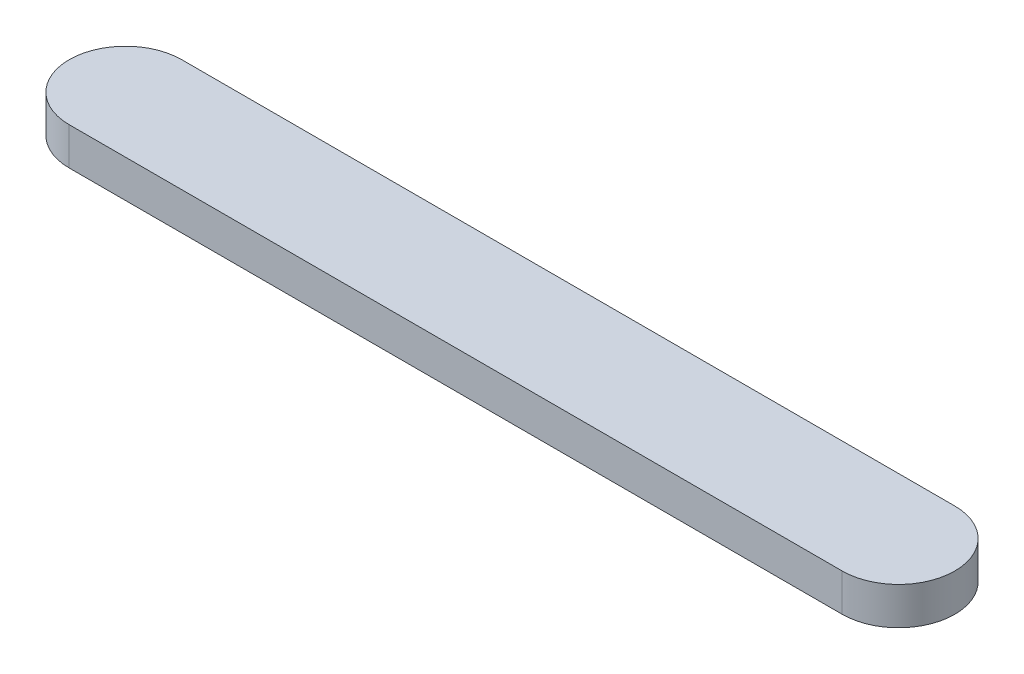
SolidWorks part; units mm, degrees
ref_plane "Plan de face" through (0, 0, 0) normal (0, 0, 1) x (1, 0, 0)
ref_plane "Plan de dessus" through (0, 0, 0) normal (0, 1, 0) x (1, 0, 0)
ref_plane "Plan de droite" through (0, 0, 0) normal (1, 0, 0) x (0, 0, -1)
sketch "Esquisse1" plane through (0, 0, 0) normal (0, 1, 0) x (1, 0, 0)
  line L0 (-103, -15) -> (103, -15)
  line L1 (-103, -15) -> (-103, 15) construction
  line L2 (103, -15) -> (103, 15) construction
  line L3 (-103, 15) -> (103, 15)
  line L4 (-103, -15) -> (103, 15) construction
  line L5 (103, -15) -> (-103, 15) construction
  arc A0 (103, 15) -> (103, -15) centre (103, 0) cw
  arc A1 (-103, 15) -> (-103, -15) centre (-103, 0) ccw
  point P1 (0, 0)
  dimension "D1" = 103
  dimension "D2" = 30
extrude "Boss.-Extru.1" add sketch "Esquisse1" along normal blind 10
